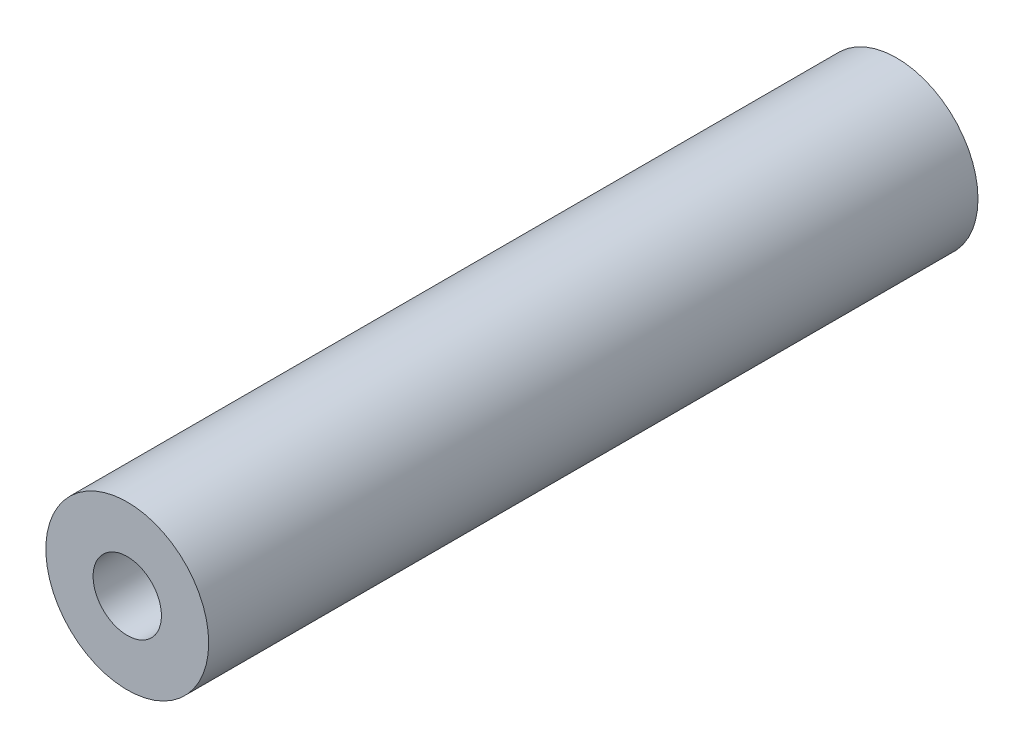
SolidWorks part; units mm, degrees
ref_plane "Front" through (0, 0, 0) normal (0, 0, 1) x (1, 0, 0)
ref_plane "Top" through (0, 0, 0) normal (0, 1, 0) x (1, 0, 0)
ref_plane "Right" through (0, 0, 0) normal (1, 0, 0) x (0, 0, -1)
sketch "Sketch1" plane through (0, 0, 0) normal (0, 0, 1) x (1, 0, 0)
  circle A0 centre (0, 0) radius 6.35
  circle A1 centre (0, 0) radius 2.665
  dimension "D1" = 12.7
  dimension "D2" = 5.33
extrude "Boss-Extrude1" add sketch "Sketch1" along normal blind 60
